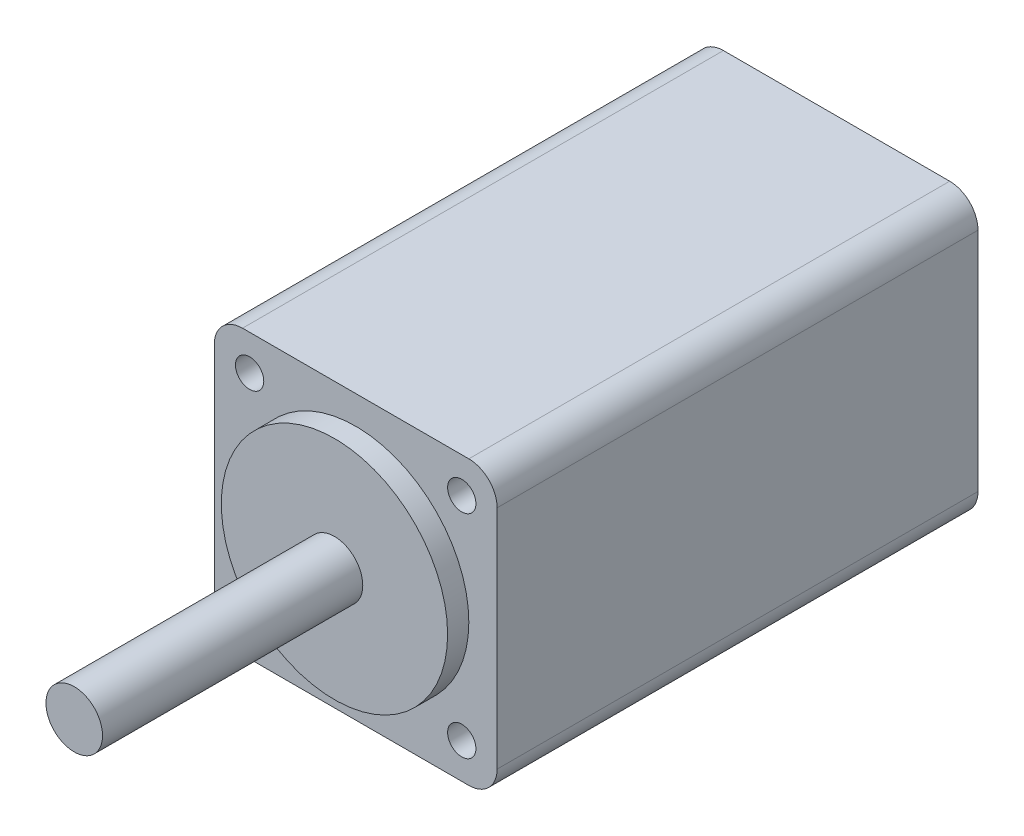
SolidWorks part; units mm, degrees
ref_plane "前基準面" through (0, 0, 0) normal (0, 0, 1) x (1, 0, 0)
ref_plane "上基準面" through (0, 0, 0) normal (0, 1, 0) x (1, 0, 0)
ref_plane "右基準面" through (0, 0, 0) normal (1, 0, 0) x (0, 0, -1)
sketch "草圖1" plane through (0, 0, 0) normal (0, 0, 1) x (1, 0, 0)
  line L1 (-21.1342, 10) -> (-1.1342, 10)
  line L2 (-21.1342, 10) -> (-21.1342, -10)
  line L3 (-21.1342, -10) -> (-1.1342, -10)
  line L4 (-1.1342, 10) -> (-1.1342, -10)
  dimension "D1" = 20
  dimension "D2" = 20
extrude "填料-伸長1" add sketch "草圖1" along normal blind 34
sketch "草圖2" plane through (0, 0, 34) normal (0, 0, 1) x (1, 0, 0)
  line L0 (-1.1342, -10) -> (-1.1342, 10) construction
  line L1 (-1.1342, 10) -> (-21.1342, 10) construction
  circle A0 centre (-11.1342, 0) radius 8
  dimension "D1" = 16
  dimension "D2" = 10
  dimension "D3" = 10
extrude "填料-伸長2" add sketch "草圖2" along normal blind 1.5
sketch "草圖3" plane through (0, 0, 35.5) normal (0, 0, 1) x (1, 0, 0)
  line L0 (-1.1342, -10) -> (-1.1342, 10) construction
  line L2 (-1.1342, 10) -> (-21.1342, 10) construction
  circle A0 centre (-11.1342, 0) radius 2
  dimension "D1" = 4
  dimension "D2" = 10
  dimension "D3" = 10
extrude "填料-伸長3" add sketch "草圖3" along normal blind 18.4
sketch "草圖4" plane through (0, 0, 34) normal (0, 0, 1) x (1, 0, 0)
  line L0 (-1.1342, 10) -> (-21.1342, 10) construction
  line L1 (-21.1342, 10) -> (-21.1342, -10) construction
  circle A0 centre (-18.6342, 7.5) radius 1
  dimension "D1" = 2
  dimension "D2" = 2.5
  dimension "D3" = 2.5
extrude "除料-伸長1" cut sketch "草圖4" against normal through all
ref_plane "平面1" through (-11.1342, 0, 0) normal (-1, 0, 0) x (0, 0, 1)
ref_plane "平面2" through (0, 0, 0) normal (0, -1, 0) x (-1, 0, 0)
mirror "鏡射1" about plane through (-11.1342, 0, 0) normal (-1, 0, 0) of "除料-伸長1"
mirror "鏡射2" about plane through (0, 0, 0) normal (0, -1, 0) of "鏡射1", "除料-伸長1"
fillet "圓角2" radius 2 4 edges at (-1.1342, -10, 17) (-21.1342, -10, 17) (-1.1342, 10, 17) (-21.1342, 10, 17)
sketch "草圖5" [suppressed] plane through (-11.1342, 0, 0) normal (-1, 0, 0) x (0, 0, 1)
  line L0 (0, 0) -> (175, 0)
  line L1 (-8.8, 0) -> (8.8, 0) construction
  dimension "D1" = 175
